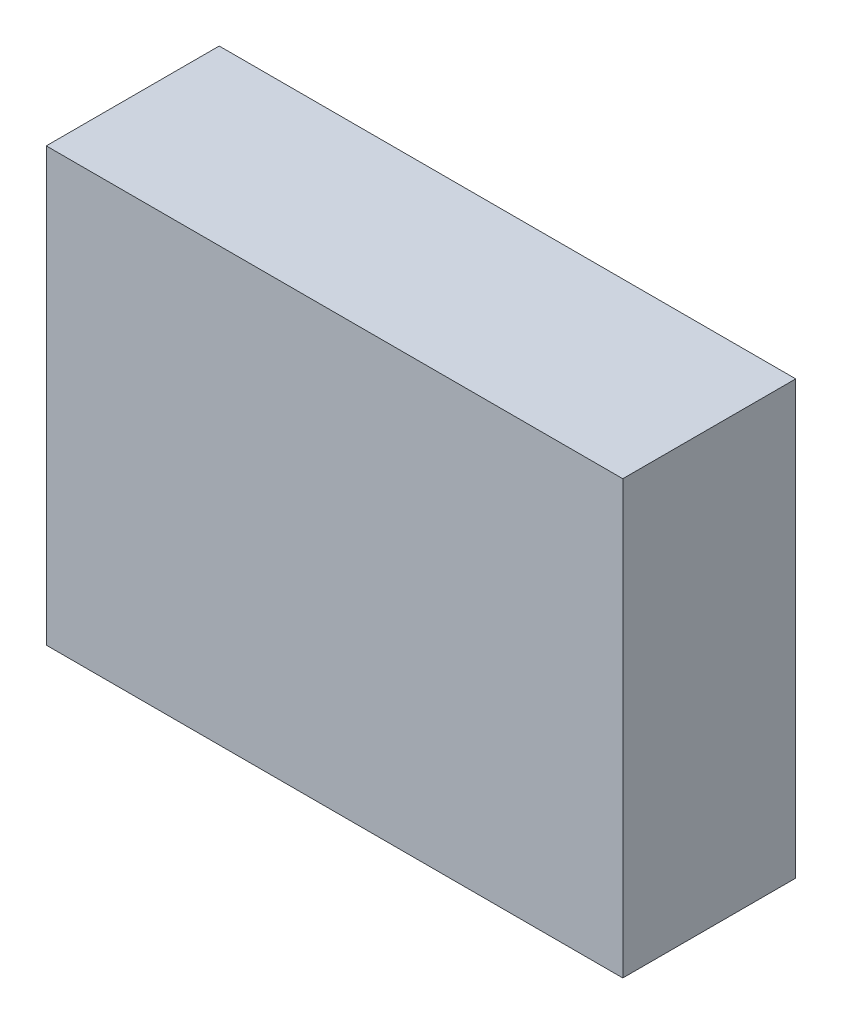
SolidWorks part; units mm, degrees
ref_plane "前视基准面" through (0, 0, 0) normal (0, 0, 1) x (1, 0, 0)
ref_plane "上视基准面" through (0, 0, 0) normal (0, 1, 0) x (1, 0, 0)
ref_plane "右视基准面" through (0, 0, 0) normal (1, 0, 0) x (0, 0, -1)
other "Configuration Table"
sketch "草图1" plane through (0, 0, 0) normal (0, 0, 1) x (1, 0, 0)
  line L0 (-20, -15) -> (20, -15)
  line L1 (20, -15) -> (20, 15)
  line L2 (20, 15) -> (-20, 15)
  line L3 (-20, 15) -> (-20, -15)
extrude "凸台-拉伸1" add sketch "草图1" along normal blind 12
sketch "草图2" plane through (0, 0, 12) normal (0, 0, 1) x (1, 0, 0)
  line L0 (-20, -15) -> (20, -15)
  line L1 (20, -15) -> (20, 15)
  line L2 (20, 15) -> (-20, 15)
  line L3 (-20, 15) -> (-20, -15)
  arc A0 (5, 0) -> (0, 5) centre (0, 0) cw
  arc A1 (0, 5) -> (-5, 0) centre (0, 0) cw
  arc A2 (-5, 0) -> (0, -5) centre (0, 0) cw
  arc A3 (0, -5) -> (5, 0) centre (0, 0) cw
